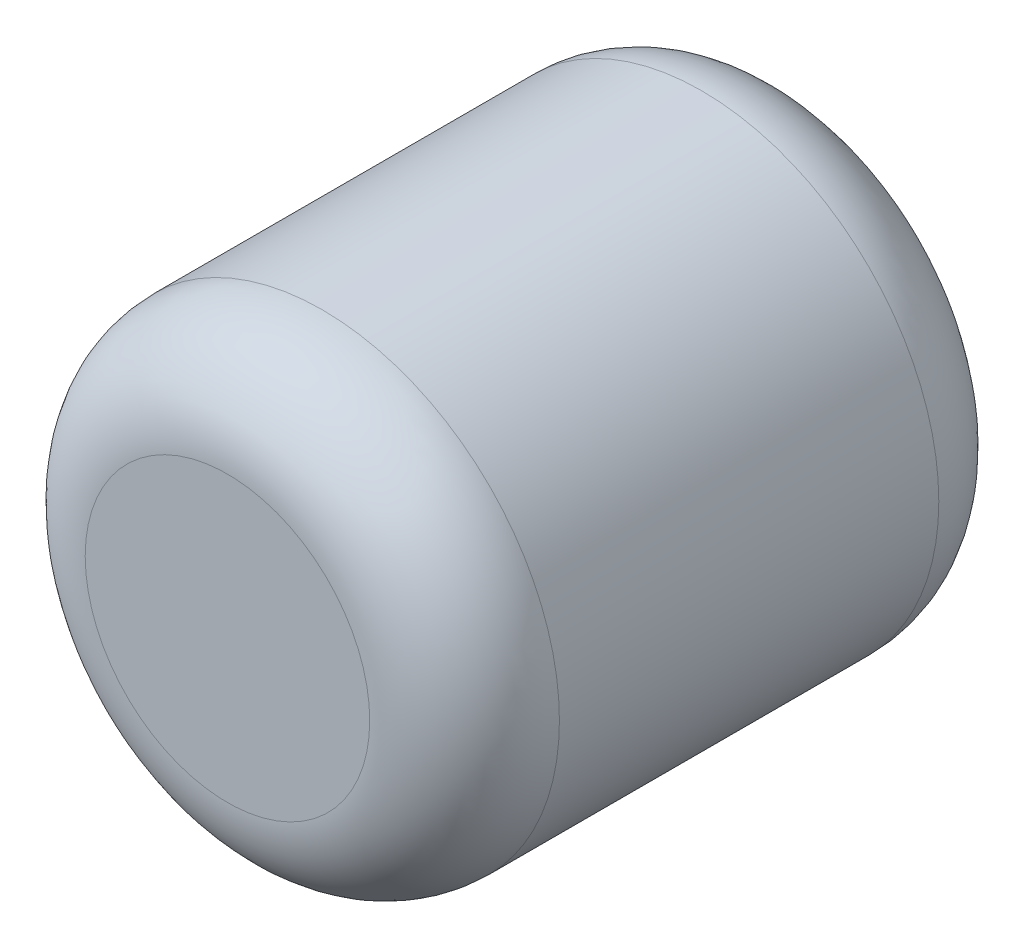
SolidWorks part; units mm, degrees
ref_plane "Plan de face" through (0, 0, 0) normal (0, 0, 1) x (1, 0, 0)
ref_plane "Plan de dessus" through (0, 0, 0) normal (0, 1, 0) x (1, 0, 0)
ref_plane "Plan de droite" through (0, 0, 0) normal (1, 0, 0) x (0, 0, -1)
sketch "Esquisse1" plane through (0, 0, 0) normal (0, 0, 1) x (1, 0, 0)
  circle A0 centre (0, 0) radius 63.5
  dimension "D1" = 127
extrude "Boss.-Extru.1" add sketch "Esquisse1" along normal blind 152.4
fillet "Congé1" radius 25.4 2 edges at (63.5, 0, 0) (63.5, 0, 152.4)
